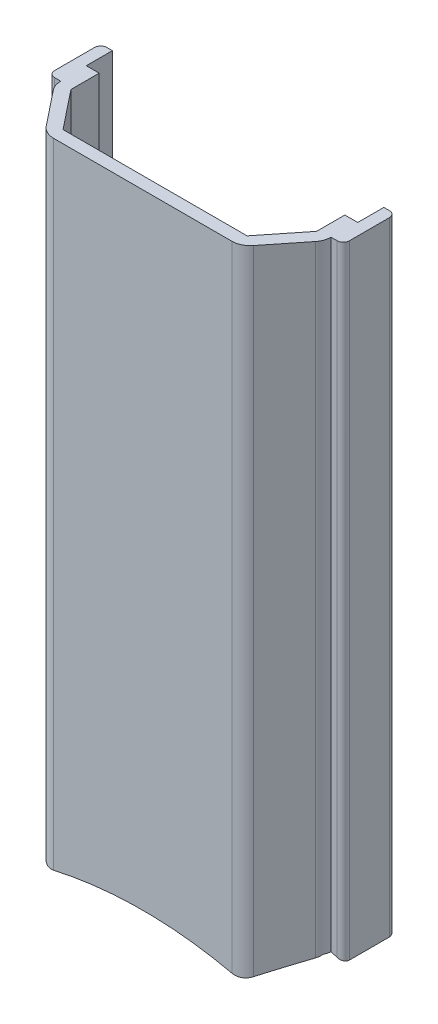
SolidWorks part; units mm, degrees
ref_plane "前视基准面" through (0, 0, 0) normal (0, 0, 1) x (1, 0, 0)
ref_plane "上视基准面" through (0, 0, 0) normal (0, 1, 0) x (1, 0, 0)
ref_plane "右视基准面" through (0, 0, 0) normal (1, 0, 0) x (0, 0, -1)
other "Configuration Table"
sketch "草图1" plane through (0, 0, 0) normal (0, 1, 0) x (1, 0, 0)
  line L5 (21.3466, -10.7196) -> (16.852, -16.3628)
  line L7 (20, -4.6001) -> (22, -4.6001)
  line L9 (20, -9.2001) -> (20, -4.6001)
  line L10 (14.9873, -15.4937) -> (20, -9.2001)
  line L11 (14.5054, -17.4937) -> (-14.5054, -17.4937)
  line L12 (-14.9873, -15.4937) -> (14.9873, -15.4937)
  line L14 (-20, -9.2001) -> (-14.9873, -15.4937)
  line L15 (-20, -4.6001) -> (-20, -9.2001)
  line L17 (-22.1, -0.3496) -> (-23, -0.3496)
  line L18 (-24, -1.3496) -> (-24, -7.8505)
  line L20 (-22, -4.6001) -> (-22.1, -4.6001)
  line L21 (-22.1, -4.6001) -> (-22.1, -0.3496)
  line L22 (22.1, -0.3496) -> (23, -0.3496)
  line L23 (24, -1.3496) -> (24, -7.8505)
  line L41 (22, -4.6001) -> (22.1, -4.6001)
  line L42 (22.1, -4.6001) -> (22.1, -0.3496)
  line L43 (-16.852, -16.3628) -> (-21.3466, -10.7196)
  line L57 (-22, -4.6001) -> (-20, -4.6001)
  line L59 (-22, -8.8505) -> (-23, -8.8505)
  line L61 (22, -8.8505) -> (23, -8.8505)
  arc A2 (23, -8.8505) -> (24, -7.8505) centre (23, -7.8505) ccw
  arc A3 (24, -1.3496) -> (23, -0.3496) centre (23, -1.3496) ccw
  arc A12 (16.852, -16.3628) -> (14.5054, -17.4937) centre (14.5054, -14.4937) cw
  arc A14 (-14.5054, -17.4937) -> (-16.852, -16.3628) centre (-14.5054, -14.4937) cw
  arc A16 (-23, -8.8505) -> (-24, -7.8505) centre (-23, -7.8505) cw
  arc A17 (-23, -0.3496) -> (-24, -1.3496) centre (-23, -1.3496) ccw
  arc A19 (21.3466, -10.7196) -> (22, -8.8505) centre (19, -8.8505) ccw
  arc A20 (-22, -8.8505) -> (-21.3466, -10.7196) centre (-19, -8.8505) ccw
  dimension "D3" = 0.1
  dimension "D2" = 0.1
extrude "凸台-拉伸1" add sketch "草图1" along normal up to surface (58.8974 mm away)
sketch "草图2" plane through (0, 0, 0) normal (0, -1, 0) x (1, 0, 0)
  line L18 (23, 8.8505) -> (22, 8.8505)
  line L19 (-24, 7.8505) -> (-24, 1.3496)
  line L20 (-23, 0.3496) -> (-22.1, 0.3496)
  line L21 (-22.1, 0.3496) -> (-22.1, 4.6001)
  line L22 (-22.1, 4.6001) -> (-20, 4.6001)
  line L23 (-20, 4.6001) -> (-20, 9.2001)
  line L24 (-20, 9.2001) -> (-14.9873, 15.4937)
  line L25 (-14.9873, 15.4937) -> (14.9873, 15.4937)
  line L26 (14.9873, 15.4937) -> (20, 9.2001)
  line L27 (20, 9.2001) -> (20, 4.6001)
  line L28 (20, 4.6001) -> (22.1, 4.6001)
  line L29 (22.1, 4.6001) -> (22.1, 0.3496)
  line L30 (22.1, 0.3496) -> (23, 0.3496)
  line L31 (24, 1.3496) -> (24, 7.8505)
  line L32 (23, 8.8505) -> (22, 8.8505)
  line L33 (21.3466, 10.7196) -> (16.852, 16.3628)
  line L34 (14.5054, 17.4937) -> (-14.5054, 17.4937)
  line L37 (-24, 7.8505) -> (-24, 1.3496)
  line L38 (-23, 0.3496) -> (-22.1, 0.3496)
  line L39 (-22.1, 0.3496) -> (-22.1, 4.6001)
  line L40 (-22.1, 4.6001) -> (-20, 4.6001)
  line L41 (-20, 4.6001) -> (-20, 9.2001)
  line L42 (-20, 9.2001) -> (-14.9873, 15.4937)
  line L43 (-14.9873, 15.4937) -> (14.9873, 15.4937)
  line L44 (14.9873, 15.4937) -> (20, 9.2001)
  line L45 (20, 9.2001) -> (20, 4.6001)
  line L46 (20, 4.6001) -> (22.1, 4.6001)
  line L47 (22.1, 4.6001) -> (22.1, 0.3496)
  line L48 (22.1, 0.3496) -> (23, 0.3496)
  line L49 (24, 1.3496) -> (24, 7.8505)
  line L51 (21.3466, 10.7196) -> (16.852, 16.3628)
  line L52 (14.5054, 17.4937) -> (-14.5054, 17.4937)
  line L57 (-16.852, 16.3628) -> (-21.3466, 10.7196)
  line L58 (-16.852, 16.3628) -> (-21.3466, 10.7196)
  line L61 (-22, 8.8505) -> (-23, 8.8505)
  line L62 (-22, 8.8505) -> (-23, 8.8505)
  arc A8 (-21.3466, 10.7196) -> (-22, 8.8505) centre (-19, 8.8505) ccw
  arc A9 (-21.3466, 10.7196) -> (-22, 8.8505) centre (-19, 8.8505) ccw
  arc A10 (22, 8.8505) -> (21.3466, 10.7196) centre (19, 8.8505) ccw
  arc A11 (22, 8.8505) -> (21.3466, 10.7196) centre (19, 8.8505) ccw
  arc A12 (-23, 8.8505) -> (-24, 7.8505) centre (-23, 7.8505) ccw
  arc A13 (-24, 1.3496) -> (-23, 0.3496) centre (-23, 1.3496) ccw
  arc A14 (23, 0.3496) -> (24, 1.3496) centre (23, 1.3496) ccw
  arc A15 (24, 7.8505) -> (23, 8.8505) centre (23, 7.8505) ccw
  arc A18 (16.852, 16.3628) -> (14.5054, 17.4937) centre (14.5054, 14.4937) ccw
  arc A19 (-14.5054, 17.4937) -> (-16.852, 16.3628) centre (-14.5054, 14.4937) ccw
  arc A22 (-23, 8.8505) -> (-24, 7.8505) centre (-23, 7.8505) ccw
  arc A23 (-24, 1.3496) -> (-23, 0.3496) centre (-23, 1.3496) ccw
  arc A24 (23, 0.3496) -> (24, 1.3496) centre (23, 1.3496) ccw
  arc A25 (24, 7.8505) -> (23, 8.8505) centre (23, 7.8505) ccw
  arc A28 (16.852, 16.3628) -> (14.5054, 17.4937) centre (14.5054, 14.4937) ccw
  arc A29 (-14.5054, 17.4937) -> (-16.852, 16.3628) centre (-14.5054, 14.4937) ccw
  dimension "D1" = 0
extrude "凸台-拉伸2" add sketch "草图2" along normal up to surface (38.3996 mm away)
ref_plane "基准面1" through (0, -38.3996, 0) normal (0, -1, 0) x (-1, 0, 0)
sketch "草图3" plane through (0, 0, 4.6001) normal (0, 0, -1) x (-1, 0, 0)
  line L0 (22.1, -38.3996) -> (22.1, -35.3996)
  line L1 (22.1, 58.8974) -> (22.1, -38.3996) construction
  line L2 (22.1, -35.3996) -> (-22.1, -35.3996)
  line L3 (-22.1, 58.8974) -> (-22.1, -38.3996) construction
  line L4 (-22.1, -35.3996) -> (-22.1, -38.3996)
  line L5 (-22.1, -38.3996) -> (22.1, -38.3996)
  dimension "D1" = 3
extrude "凸台-拉伸3" add sketch "草图3" against normal up to surface (12.8937 mm away) up to face at (0, 10.2489, 17.4937)
sketch "草图4" plane through (0, 0, 4.6001) normal (0, 0, -1) x (-1, 0, 0)
  line L0 (22.1, 38.8974) -> (-22.1, 38.8974)
  line L3 (22.1, 58.8974) -> (22.1, -38.3996) construction
  line L4 (22.1, 38.8974) -> (22.1, 35.8974)
  line L7 (-22.1, 58.8974) -> (-22.1, -38.3996) construction
  line L8 (-22.1, 38.8974) -> (-22.1, 35.8974)
  line L9 (-22.1, 35.8974) -> (22.1, 35.8974)
  dimension "D2" = 3
extrude "凸台-拉伸4" add sketch "草图4" against normal up to surface (12.8937 mm away) up to face at (0, -12.5754, 17.4937)
sketch "草图5" plane through (0, 38.8974, 0) normal (0, 1, 0) x (1, 0, 0)
  line L3 (-22, -8.8505) -> (-22.1, -8.8505)
  line L4 (-22.1, -8.8505) -> (-22.1, -17.4937)
  line L5 (-22.1, -17.4937) -> (-14.5054, -17.4937)
  line L7 (-22.1, -8.8505) -> (-22.1, -17.4937)
  line L8 (-22.1, -17.4937) -> (-14.5054, -17.4937)
  line L9 (14.5054, -17.4937) -> (22.1, -17.4937)
  line L10 (22.1, -17.4937) -> (22.1, -8.8505)
  line L11 (21.3466, -10.7196) -> (16.852, -16.3628)
  line L12 (14.5054, -17.4937) -> (22.1, -17.4937)
  line L13 (22.1, -17.4937) -> (22.1, -8.8505)
  line L14 (21.3466, -10.7196) -> (16.852, -16.3628)
  line L17 (-22, -8.8505) -> (-22.1, -8.8505)
  line L18 (-16.852, -16.3628) -> (-21.3466, -10.7196)
  line L19 (-16.852, -16.3628) -> (-21.3466, -10.7196)
  line L22 (22.1, -8.8505) -> (22, -8.8505)
  line L23 (22.1, -8.8505) -> (22, -8.8505)
  arc A2 (-22, -8.8505) -> (-21.3466, -10.7196) centre (-19, -8.8505) ccw
  arc A3 (-16.852, -16.3628) -> (-14.5054, -17.4937) centre (-14.5054, -14.4937) ccw
  arc A4 (-22, -8.8505) -> (-21.3466, -10.7196) centre (-19, -8.8505) ccw
  arc A5 (21.3466, -10.7196) -> (22, -8.8505) centre (19, -8.8505) ccw
  arc A6 (-16.852, -16.3628) -> (-14.5054, -17.4937) centre (-14.5054, -14.4937) ccw
  arc A9 (14.5054, -17.4937) -> (16.852, -16.3628) centre (14.5054, -14.4937) ccw
  arc A10 (21.3466, -10.7196) -> (22, -8.8505) centre (19, -8.8505) ccw
  arc A12 (14.5054, -17.4937) -> (16.852, -16.3628) centre (14.5054, -14.4937) ccw
  dimension "D1" = 0
  dimension "D2" = 0
extrude "切除-拉伸1" cut sketch "草图5" against normal up to surface (77.297 mm away) contours A6 L8 L7 L17 A4 L19 | A12 L14 A10 L23 L13 L12 up to face at (0, -38.3996, 6.2118)
sketch "草图6" plane through (0, 38.8974, 0) normal (0, 1, 0) x (1, 0, 0)
  line L12 (8.0613, -11.7949) -> (8.0613, -7.4001)
  line L13 (8.0613, -7.4001) -> (-8.0613, -7.4001)
  line L14 (-8.0613, -7.4001) -> (-8.0613, -11.7949)
  line L15 (-8.0613, -11.7949) -> (8.0613, -11.7949)
extrude "切除-拉伸2" cut sketch "草图6" against normal up to surface (3 mm away) up to face at (0, 35.8974, 9.7646)
sketch "草图7" plane through (0, -38.3996, 0) normal (0, -1, 0) x (-1, 0, 0)
  line L20 (20, -4.6001) -> (20, -9.2001)
  line L21 (22, -4.6001) -> (20, -4.6001)
  line L22 (22.1, -4.6001) -> (22, -4.6001)
  line L23 (22.1, -0.3496) -> (22.1, -4.6001)
  line L24 (23, -0.3496) -> (22.1, -0.3496)
  line L25 (24, -7.8505) -> (24, -1.3496)
  line L26 (22, -8.8505) -> (23, -8.8505)
  line L27 (16.852, -16.3628) -> (21.3466, -10.7196)
  line L28 (-14.5054, -17.4937) -> (14.5054, -17.4937)
  line L29 (-21.3466, -10.7196) -> (-16.852, -16.3628)
  line L30 (-23, -8.8505) -> (-22, -8.8505)
  line L31 (-24, -1.3496) -> (-24, -7.8505)
  line L32 (-22.1, -0.3496) -> (-23, -0.3496)
  line L33 (-22.1, -4.6001) -> (-22.1, -0.3496)
  line L34 (-22, -4.6001) -> (-22.1, -4.6001)
  line L35 (-20, -4.6001) -> (-22, -4.6001)
  line L36 (-20, -9.2001) -> (-20, -4.6001)
  line L37 (-14.9873, -15.4937) -> (-20, -9.2001)
  line L38 (14.9873, -15.4937) -> (-14.9873, -15.4937)
  line L39 (20, -9.2001) -> (14.9873, -15.4937)
  line L40 (20, -4.6001) -> (20, -9.2001)
  line L41 (22, -4.6001) -> (20, -4.6001)
  line L42 (22.1, -4.6001) -> (22, -4.6001)
  line L43 (22.1, -0.3496) -> (22.1, -4.6001)
  line L44 (23, -0.3496) -> (22.1, -0.3496)
  line L45 (24, -7.8505) -> (24, -1.3496)
  line L46 (22, -8.8505) -> (23, -8.8505)
  line L47 (16.852, -16.3628) -> (21.3466, -10.7196)
  line L48 (-14.5054, -17.4937) -> (14.5054, -17.4937)
  line L49 (-21.3466, -10.7196) -> (-16.852, -16.3628)
  line L50 (-23, -8.8505) -> (-22, -8.8505)
  line L51 (-24, -1.3496) -> (-24, -7.8505)
  line L52 (-22.1, -0.3496) -> (-23, -0.3496)
  line L53 (-22.1, -4.6001) -> (-22.1, -0.3496)
  line L54 (-22, -4.6001) -> (-22.1, -4.6001)
  line L55 (-20, -4.6001) -> (-22, -4.6001)
  line L56 (-20, -9.2001) -> (-20, -4.6001)
  line L57 (-14.9873, -15.4937) -> (-20, -9.2001)
  line L58 (14.9873, -15.4937) -> (-14.9873, -15.4937)
  line L59 (20, -9.2001) -> (14.9873, -15.4937)
  arc A8 (24, -1.3496) -> (23, -0.3496) centre (23, -1.3496) ccw
  arc A9 (23, -8.8505) -> (24, -7.8505) centre (23, -7.8505) ccw
  arc A10 (21.3466, -10.7196) -> (22, -8.8505) centre (19, -8.8505) ccw
  arc A11 (14.5054, -17.4937) -> (16.852, -16.3628) centre (14.5054, -14.4937) ccw
  arc A12 (-16.852, -16.3628) -> (-14.5054, -17.4937) centre (-14.5054, -14.4937) ccw
  arc A13 (-22, -8.8505) -> (-21.3466, -10.7196) centre (-19, -8.8505) ccw
  arc A14 (-24, -7.8505) -> (-23, -8.8505) centre (-23, -7.8505) ccw
  arc A15 (-23, -0.3496) -> (-24, -1.3496) centre (-23, -1.3496) ccw
  arc A16 (24, -1.3496) -> (23, -0.3496) centre (23, -1.3496) ccw
  arc A17 (23, -8.8505) -> (24, -7.8505) centre (23, -7.8505) ccw
  arc A18 (21.3466, -10.7196) -> (22, -8.8505) centre (19, -8.8505) ccw
  arc A19 (14.5054, -17.4937) -> (16.852, -16.3628) centre (14.5054, -14.4937) ccw
  arc A20 (-16.852, -16.3628) -> (-14.5054, -17.4937) centre (-14.5054, -14.4937) ccw
  arc A21 (-22, -8.8505) -> (-21.3466, -10.7196) centre (-19, -8.8505) ccw
  arc A22 (-24, -7.8505) -> (-23, -8.8505) centre (-23, -7.8505) ccw
  arc A23 (-23, -0.3496) -> (-24, -1.3496) centre (-23, -1.3496) ccw
  dimension "D1" = 0
extrude "凸台-拉伸5" add sketch "草图7" along normal blind 15
sketch "草图8" plane through (0, 0, 0) normal (1, 0, 0) x (0, 0, -1)
  line L14 (-9.8992, -38.2996) -> (-20.2915, -44.2996)
  line L18 (-9.8992, -40.3996) -> (-9.8992, -176.3996) construction
  line L19 (-20.2915, -44.3996) -> (-20.2915, -172.3996) construction
  line L20 (-20.2915, -44.2996) -> (-20.2915, -55.8019)
  line L21 (-9.8992, -108.3996) -> (14.8215, -108.3996) construction
  line L22 (-20.2915, -46.3996) -> (-20.2915, -170.3996) construction
  line L23 (-20.2915, -55.8019) -> (11.0914, -55.8019)
  line L25 (0.6991, -38.2996) -> (-9.8992, -38.2996)
  line L26 (-4.6001, 35.8974) -> (-4.6001, -35.3996) construction
  line L27 (11.0914, -44.2996) -> (11.0914, -55.8019)
  line L28 (0.6991, -38.2996) -> (11.0914, -44.2996)
revolve "切除-旋转1" cut sketch "草图8" angle 360 about L21
